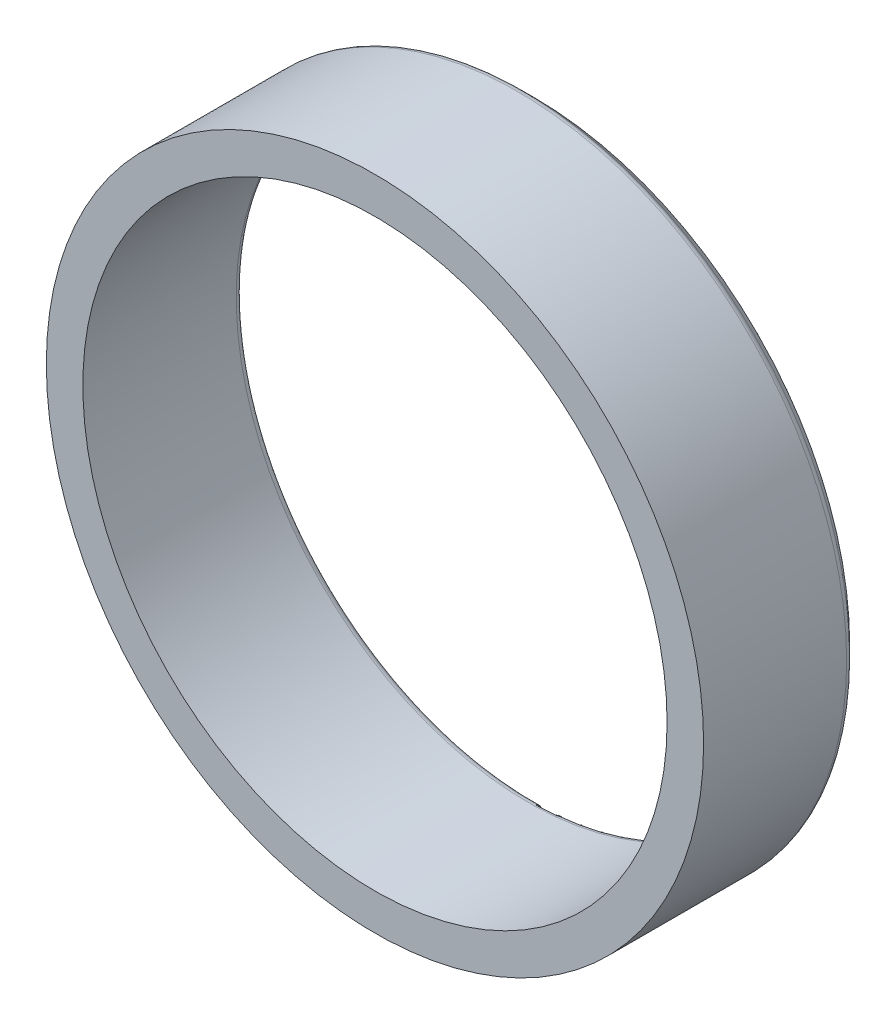
SolidWorks part; units mm, degrees
material "moto_yellow"
ref_plane "Front Plane" through (0, 0, 0) normal (0, 0, 1) x (1, 0, 0)
ref_plane "Top Plane" through (0, 0, 0) normal (0, 1, 0) x (1, 0, 0)
ref_plane "Right Plane" through (0, 0, 0) normal (1, 0, 0) x (0, 0, -1)
sketch "Sketch1" plane through (0, 0, 0) normal (0, 0, 1) x (1, 0, 0)
  circle A0 centre (0, 0) radius 45
  circle A1 centre (0, 0) radius 40
  dimension "D1" = 90
  dimension "D2" = 5
extrude "Boss-Extrude1" add sketch "Sketch1" along normal blind 22
chamfer "Chamfer1" distance 2 angle 45 1 edges at (45, 0, 0)
fillet "Fillet1" radius 1 3 edges at (45, 0, 2) (40, 0, 0) (43, 0, 0)
